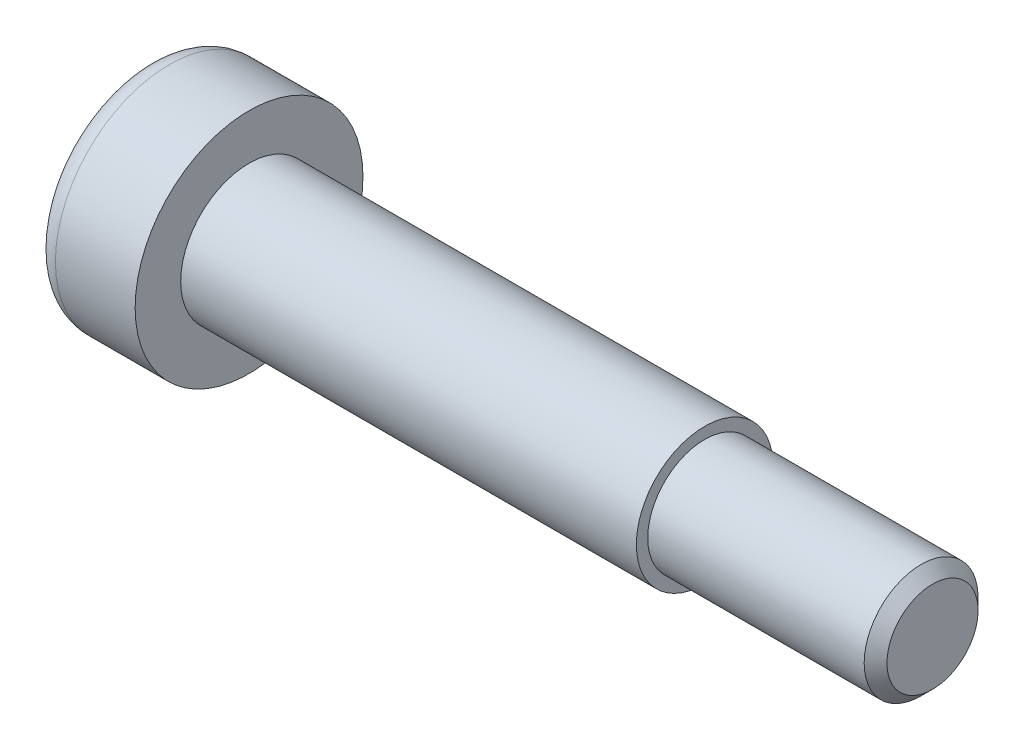
SolidWorks part; units mm, degrees
material "不锈钢 (铁素体)"
ref_plane "前视基准面" through (0, 0, 0) normal (0, 0, 1) x (1, 0, 0)
ref_plane "上视基准面" through (0, 0, 0) normal (0, 1, 0) x (1, 0, 0)
ref_plane "右视基准面" through (0, 0, 0) normal (1, 0, 0) x (0, 0, -1)
sketch "草图1" plane through (0, 0, 0) normal (0, 0, 1) x (1, 0, 0)
  line L0 (0, 0) -> (34.5, 0) construction
  line L1 (0, 0) -> (0, 5)
  line L2 (0, 5) -> (4.5, 5)
  line L3 (4.5, 5) -> (4.5, 3)
  line L4 (4.5, 3) -> (24.5, 3)
  line L5 (24.5, 3) -> (24.5, 2.5)
  line L6 (24.5, 2.5) -> (34.5, 2.5)
  line L7 (34.5, 2.5) -> (34.5, 0)
  line L8 (0, 0) -> (34.5, 0)
  dimension "D1" = 10
  dimension "D2" = 6
  dimension "D3" = 5
  dimension "D4" = 10
  dimension "D5" = 4.5
  dimension "D6" = 20
revolve "旋转1" add sketch "草图1" angle 360 about L0
cosmetic thread "装饰螺纹线1" parameters "D2"=4.134
sketch "草图2" plane through (0, 0, 0) normal (-1, 0, 0) x (0, 0, 1)
  line L0 (0, 0) -> (0, 1.7321) construction
  line L1 (0, 1.7321) -> (-1.5, 0.866)
  line L2 (-1.5, 0.866) -> (-1.5, -0.866)
  line L3 (-1.5, -0.866) -> (0, -1.7321)
  line L4 (0, -1.7321) -> (1.5, -0.866)
  line L5 (1.5, -0.866) -> (1.5, 0.866)
  line L6 (1.5, 0.866) -> (0, 1.7321)
  circle A0 centre (0, 0) radius 1.5 construction
  dimension "D1" = 3
extrude "切除-拉伸1" cut sketch "草图2" against normal blind 3
fillet "圆角1" radius 1 1 edges at (0, 0, 5)
chamfer "倒角1" distance 0.5 angle 45 1 edges at (34.5, 0, 2.5)
